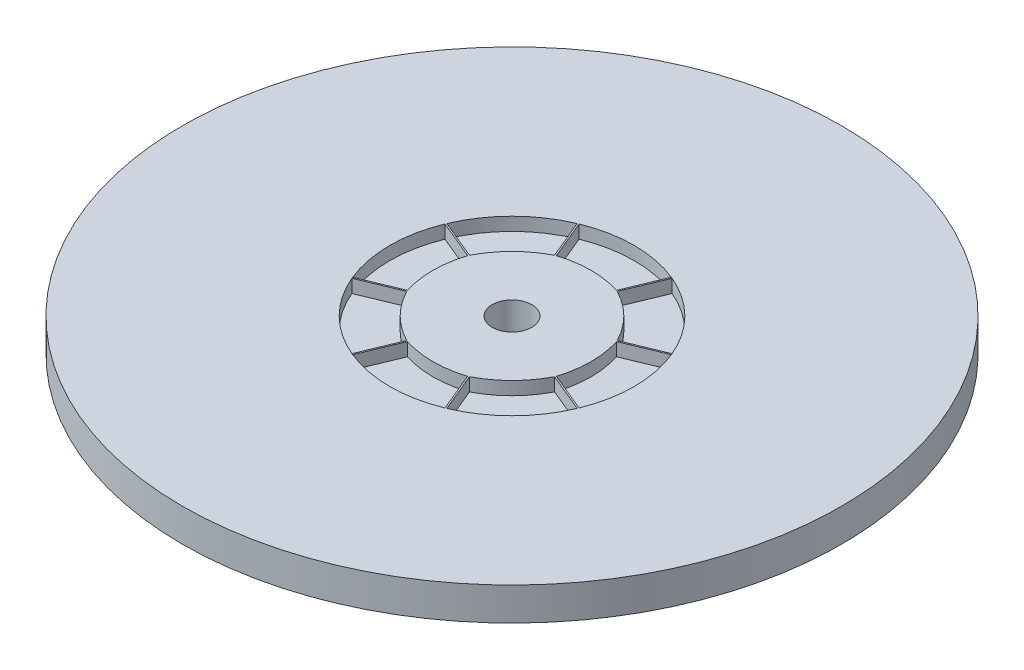
SolidWorks part; units mm, degrees
material "AISI 316 Stainless Steel Sheet (SS)"
ref_plane "Front Plane" through (0, 0, 0) normal (0, 0, 1) x (1, 0, 0)
ref_plane "Top Plane" through (0, 0, 0) normal (0, 1, 0) x (1, 0, 0)
ref_plane "Right Plane" through (0, 0, 0) normal (1, 0, 0) x (0, 0, -1)
sketch "Sketch1" plane through (0, 0, 0) normal (1, 0, 0) x (0, 0, -1)
  line L0 (0, 285.5556) -> (0, 25) construction
  line L1 (-500, 25) -> (-500, -25)
  line L2 (-500, 25) -> (-30, 25)
  line L3 (-500, -25) -> (-30, -25)
  line L4 (0, 25) -> (0, -25) construction
  line L5 (-30, 25) -> (-30, -25)
  line L6 (-30, -25) -> (0, -25) construction
  line L7 (0, 25) -> (0, -25) construction
  line L8 (0, -25) -> (0, -214.4444) construction
  line L9 (-30, 25) -> (0, 25) construction
  point P5 (-500, 0)
  dimension "D1" = 1000
  dimension "D2" = 50
  dimension "D3" = 30
revolve "Revolve1" add sketch "Sketch1" angle 360 about L0
sketch "Sketch2" plane through (0, -25, 0) normal (0, -1, 0) x (1, 0, 0)
  line L0 (0, 0) -> (0, 604.4151) construction
  line L1 (-180, 446.4762) -> (-122.573, 307.8351)
  line L2 (122.573, 307.8351) -> (180, 446.4762)
  line L3 (188.4271, 442.9855) -> (131.0001, 304.3445)
  line L4 (304.3445, 131.0001) -> (442.9855, 188.4271)
  line L5 (446.4762, 180) -> (307.8351, 122.573)
  line L6 (307.8351, -122.573) -> (446.4762, -180)
  line L7 (442.9855, -188.4271) -> (304.3445, -131.0001)
  line L8 (131.0001, -304.3445) -> (188.4271, -442.9855)
  line L9 (180, -446.4762) -> (122.573, -307.8351)
  line L10 (-122.573, -307.8351) -> (-180, -446.4762)
  line L11 (-188.4271, -442.9855) -> (-131.0001, -304.3445)
  line L12 (-304.3445, -131.0001) -> (-442.9855, -188.4271)
  line L13 (-446.4762, -180) -> (-307.8351, -122.573)
  line L14 (-307.8351, 122.573) -> (-446.4762, 180)
  line L15 (-442.9855, 188.4271) -> (-304.3445, 131.0001)
  line L16 (-131.0001, 304.3445) -> (-188.4271, 442.9855)
  arc A1 (-122.573, 307.8351) -> (122.573, 307.8351) centre (0, -20) cw
  arc A2 (180, 446.4762) -> (-180, 446.4762) centre (0, -20) ccw
  arc A3 (442.9855, 188.4271) -> (188.4271, 442.9855) centre (-14.1421, -14.1421) ccw
  arc A4 (131.0001, 304.3445) -> (304.3445, 131.0001) centre (-14.1421, -14.1421) cw
  arc A5 (446.4762, -180) -> (446.4762, 180) centre (-20, 0) ccw
  arc A6 (307.8351, 122.573) -> (307.8351, -122.573) centre (-20, 0) cw
  arc A7 (188.4271, -442.9855) -> (442.9855, -188.4271) centre (-14.1421, 14.1421) ccw
  arc A8 (304.3445, -131.0001) -> (131.0001, -304.3445) centre (-14.1421, 14.1421) cw
  arc A9 (-180, -446.4762) -> (180, -446.4762) centre (0, 20) ccw
  arc A10 (122.573, -307.8351) -> (-122.573, -307.8351) centre (0, 20) cw
  arc A11 (-442.9855, -188.4271) -> (-188.4271, -442.9855) centre (14.1421, 14.1421) ccw
  arc A12 (-131.0001, -304.3445) -> (-304.3445, -131.0001) centre (14.1421, 14.1421) cw
  arc A13 (-446.4762, 180) -> (-446.4762, -180) centre (20, 0) ccw
  arc A14 (-307.8351, -122.573) -> (-307.8351, 122.573) centre (20, 0) cw
  arc A15 (-188.4271, 442.9855) -> (-442.9855, 188.4271) centre (14.1421, -14.1421) ccw
  arc A16 (-304.3445, 131.0001) -> (-131.0001, 304.3445) centre (14.1421, -14.1421) cw
  point P46 (0, 0)
  dimension "D1" = 500
  dimension "D2" = 350
  dimension "D3" = 45
  dimension "D4" = 360
  dimension "D5" = 20
  dimension "D6" = 8
extrude "Cut-Extrude1" [suppressed] cut sketch "Sketch2" against normal blind 20
sketch "Sketch3" plane through (0, 25, 0) normal (0, 1, 0) x (1, 0, 0)
  line L0 (0, 0) -> (0, 210.2358) construction
  line L1 (-45.6324, 112.8905) -> (-70, 171.719)
  line L2 (45.6324, 112.8905) -> (70, 171.719)
  line L3 (112.0926, 47.5586) -> (170.9212, 71.9262)
  line L4 (47.5586, 112.0926) -> (71.9262, 170.9212)
  line L5 (112.8905, -45.6324) -> (171.719, -70)
  line L6 (112.8905, 45.6324) -> (171.719, 70)
  line L7 (47.5586, -112.0926) -> (71.9262, -170.9212)
  line L8 (112.0926, -47.5586) -> (170.9212, -71.9262)
  line L9 (-45.6324, -112.8905) -> (-70, -171.719)
  line L10 (45.6324, -112.8905) -> (70, -171.719)
  line L11 (-112.0926, -47.5586) -> (-170.9212, -71.9262)
  line L12 (-47.5586, -112.0926) -> (-71.9262, -170.9212)
  line L13 (-112.8905, 45.6324) -> (-171.719, 70)
  line L14 (-112.8905, -45.6324) -> (-171.719, -70)
  line L15 (-47.5586, 112.0926) -> (-71.9262, 170.9212)
  line L16 (-112.0926, 47.5586) -> (-170.9212, 71.9262)
  arc A0 (-70, 171.719) -> (70, 171.719) centre (0, -120) cw construction
  arc A1 (-45.6324, 112.8905) -> (45.6324, 112.8905) centre (0, -30) cw
  arc A2 (71.9262, 170.9212) -> (170.9212, 71.9262) centre (-84.8528, -84.8528) cw construction
  arc A3 (47.5586, 112.0926) -> (112.0926, 47.5586) centre (-21.2132, -21.2132) cw
  arc A4 (171.719, 70) -> (171.719, -70) centre (-120, 0) cw construction
  arc A5 (112.8905, 45.6324) -> (112.8905, -45.6324) centre (-30, 0) cw
  arc A6 (170.9212, -71.9262) -> (71.9262, -170.9212) centre (-84.8528, 84.8528) cw construction
  arc A7 (112.0926, -47.5586) -> (47.5586, -112.0926) centre (-21.2132, 21.2132) cw
  arc A8 (70, -171.719) -> (-70, -171.719) centre (0, 120) cw construction
  arc A9 (45.6324, -112.8905) -> (-45.6324, -112.8905) centre (0, 30) cw
  arc A10 (-71.9262, -170.9212) -> (-170.9212, -71.9262) centre (84.8528, 84.8528) cw construction
  arc A11 (-47.5586, -112.0926) -> (-112.0926, -47.5586) centre (21.2132, 21.2132) cw
  arc A12 (-171.719, -70) -> (-171.719, 70) centre (120, 0) cw construction
  arc A13 (-112.8905, -45.6324) -> (-112.8905, 45.6324) centre (30, 0) cw
  arc A14 (-170.9212, 71.9262) -> (-71.9262, 170.9212) centre (84.8528, -84.8528) cw construction
  arc A15 (-112.0926, 47.5586) -> (-47.5586, 112.0926) centre (21.2132, -21.2132) cw
  circle A16 centre (0, 0) radius 30 construction
  arc A17 (-171.719, 70) -> (-171.719, -70) centre (0, 0) ccw
  arc A18 (-71.9262, 170.9212) -> (-170.9212, 71.9262) centre (0, 0) ccw
  arc A19 (70, 171.719) -> (-70, 171.719) centre (0, 0) ccw
  arc A20 (170.9212, 71.9262) -> (71.9262, 170.9212) centre (0, 0) ccw
  arc A21 (171.719, -70) -> (171.719, 70) centre (0, 0) ccw
  arc A22 (71.9262, -170.9212) -> (170.9212, -71.9262) centre (0, 0) ccw
  arc A23 (-70, -171.719) -> (70, -171.719) centre (0, 0) ccw
  arc A24 (-170.9212, -71.9262) -> (-71.9262, -170.9212) centre (0, 0) ccw
  point P53 (0, 0)
  dimension "D1" = 150
  dimension "D2" = 300
  dimension "D3" = 45
  dimension "D5" = 140
  dimension "D4" = 8
extrude "Cut-Extrude2" cut sketch "Sketch3" against normal blind 20
